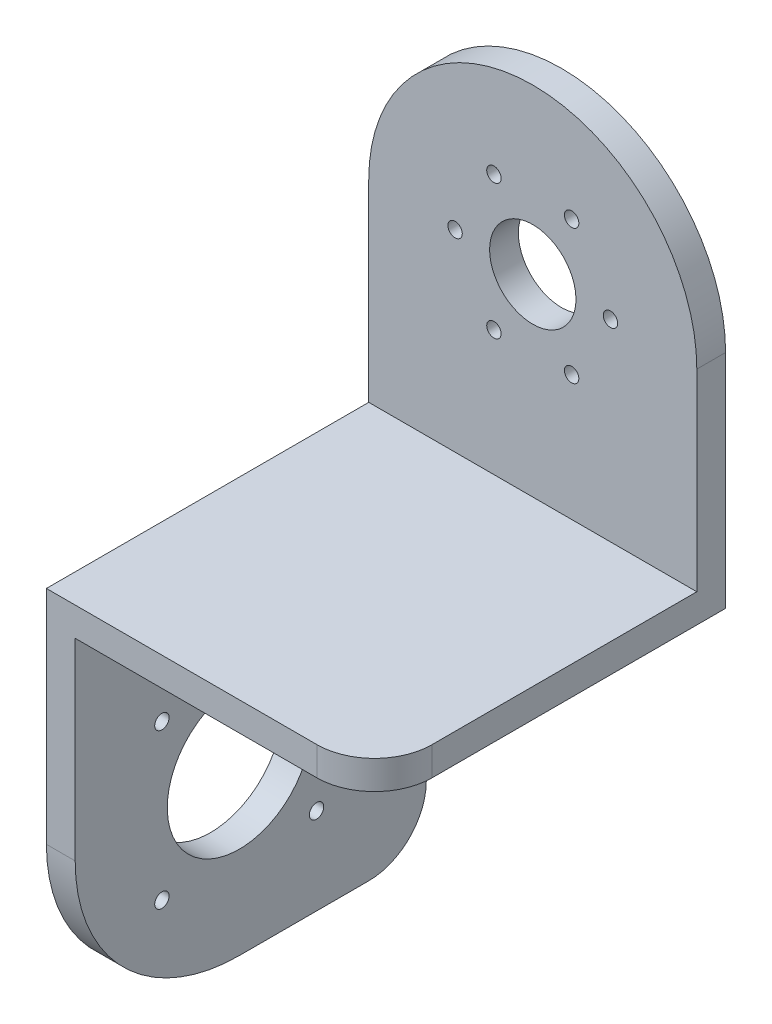
SolidWorks part; units mm, degrees
material "AISI 304"
ref_plane "前视基准面" through (0, 0, 0) normal (0, 0, 1) x (1, 0, 0)
ref_plane "上视基准面" through (0, 0, 0) normal (0, 1, 0) x (1, 0, 0)
ref_plane "右视基准面" through (0, 0, 0) normal (1, 0, 0) x (0, 0, -1)
other "Configuration Table"
sketch "草图1" plane through (0, 0, 0) normal (0, 0, 1) x (1, 0, 0)
  line L0 (0, 0) -> (57, 0)
  line L1 (57, 0) -> (57, -5)
  line L2 (57, -5) -> (5, -5)
  line L3 (0, -10.1573) -> (0, 0)
  line L4 (0, -10.1573) -> (0, -67)
  line L5 (0, -67) -> (5, -67)
  line L6 (5, -67) -> (5, -5)
  point P8 (2.5, -67)
  dimension "D1" = 67
  dimension "D2" = 57
  dimension "D3" = 5
  dimension "D4" = 5
extrude "凸台-拉伸1" add sketch "草图1" along normal blind 61
sketch "草图3" plane through (0, 0, 0) normal (-1, 0, 0) x (0, 0, 1)
  line L0 (0, 0) -> (0, 62)
  line L5 (61, 0) -> (0, 0) construction
  line L6 (0, 62) -> (5, 62)
  line L7 (5, 62) -> (5, 0)
  line L8 (5, 0) -> (0, 0)
  dimension "D4" = 5
extrude "凸台-拉伸2" add sketch "草图3" against normal blind 57
sketch "草图15" plane through (0, 0, 0) normal (0, 0, -1) x (-1, 0, 0)
  line L0 (-57, 62) -> (0, 62) construction
  line L1 (-57, -5) -> (-57, 62) construction
  line L2 (0, 62) -> (0, -67) construction
  line L3 (0, 62) -> (0, -67)
  line L4 (-57, -5) -> (-57, 62)
  line L5 (-57, 62) -> (0, 62)
  circle A0 centre (-28.5, 33.5) radius 28.5
  line M3 (0, 62) -> (-57, 62)
  line M4 (-57, 62) -> (-57, -5)
  dimension "D1" = 57
extrude "切除-拉伸11" cut sketch "草图15" against normal blind 10 contours A0 L5 M4 | A0 L3 M3
sketch "草图16" plane through (0, 0, 0) normal (0, 0, -1) x (-1, 0, 0)
  line L0 (-57, 33.5) -> (0, 33.5) construction
  line L1 (-28.5, 62) -> (-28.5, -13.2771) construction
  arc A0 (0, 33.5) -> (-57, 33.5) centre (-28.5, 33.5) ccw construction
  circle A1 centre (-28.5, 33.5) radius 7.5
  circle A2 centre (-15, 33.5) radius 1.25
  dimension "D1" = 15
  dimension "D2" = 2.5
  dimension "D3" = 13.5
extrude "切除-拉伸12" cut sketch "草图16" against normal blind 10
pattern_circular "阵列(圆周)7" count 6 over 360 about axis through (28.5, 33.5, 0) along (0, 0, 1) of "切除-拉伸12"
sketch "草图17" plane through (5, 0, 0) normal (1, 0, 0) x (0, 0, -1)
  line L0 (-61, -67) -> (-61, -5) construction
  line L1 (-61, -67) -> (0, -67) construction
  line L2 (-61, -67) -> (-61, -5)
  line L3 (-61, -67) -> (0, -67)
  circle A0 centre (-32.5, -38.5) radius 28.5
  line M5 (-61, -67) -> (0, -67)
  dimension "D1" = 57
extrude "切除-拉伸13" cut sketch "草图17" against normal blind 10 contours A0 L2 M5
fillet "圆角2" radius 10 2 edges at (57, -2.5, 61) (2.5, -67, 0)
sketch "草图18" plane through (5, 0, 0) normal (1, 0, 0) x (0, 0, -1)
  line L0 (-61, -38.5) -> (0, -38.5) construction
  line L1 (0, -57) -> (0, -5) construction
  line L2 (-32.5, -67) -> (-32.5, -19.1745) construction
  line L3 (-32.5, -38.5) -> (-61.4663, -67.4663) construction
  circle A0 centre (-32.5, -38.5) radius 12.5
  circle A1 centre (-45.935, -51.935) radius 1.25
  dimension "D1" = 25
  dimension "D3" = 2.5
  dimension "D2" = 45
  dimension "D4" = 19
extrude "切除-拉伸14" cut sketch "草图18" against normal blind 10
pattern_circular "阵列(圆周)8" count 4 over 360 about axis through (0, -38.5, 32.5) along (1, 0, 0) of "切除-拉伸14"
